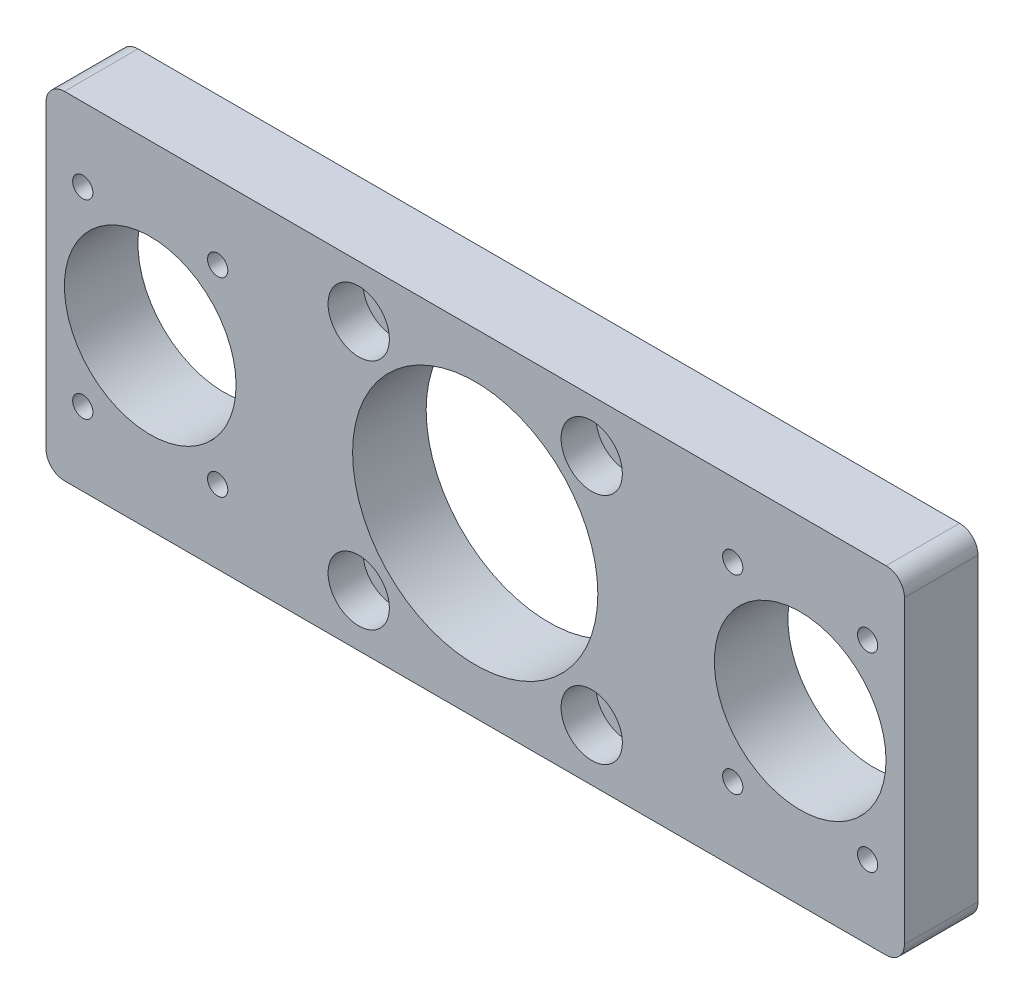
SolidWorks part; units mm, degrees
ref_plane "Front" through (0, 0, 0) normal (0, 0, 1) x (1, 0, 0)
ref_plane "Top" through (0, 0, 0) normal (0, 1, 0) x (1, 0, 0)
ref_plane "Right" through (0, 0, 0) normal (1, 0, 0) x (0, 0, -1)
sketch "草图1" plane through (0, 0, 0) normal (0, 0, 1) x (1, 0, 0)
  line L1 (-70, -27.5) -> (70, -27.5)
  line L2 (-70, -27.5) -> (-70, 27.5)
  line L3 (-70, 27.5) -> (70, 27.5)
  line L4 (70, -27.5) -> (70, 27.5)
  line L5 (-70, -27.5) -> (70, 27.5) construction
  line L6 (-70, 27.5) -> (70, -27.5) construction
  point P0 (0, 0)
  dimension "D1" = 55
  dimension "D2" = 140
extrude "凸台-拉伸1" add sketch "草图1" along normal blind 12
sketch "草图2" plane through (0, 0, 12) normal (0, 0, 1) x (1, 0, 0)
  line L0 (-70, 27.5) -> (-70, -27.5) construction
  line L1 (70, -27.5) -> (70, 27.5) construction
  circle A0 centre (0, 0) radius 20
  circle A1 centre (-53, 0) radius 14
  circle A2 centre (53, 0) radius 14
  dimension "D1" = 40
  dimension "D2" = 28
  dimension "D3" = 28
  dimension "D4" = 17
  dimension "D5" = 17
extrude "切除-拉伸1" cut sketch "草图2" against normal through all
fillet "圆角1" radius 3 4 edges at (70, 27.5, 6) (70, -27.5, 6) (-70, -27.5, 6) (-70, 27.5, 6)
sketch "草图3" plane through (0, 0, 12) normal (0, 0, 1) x (1, 0, 0)
  line L1 (-64, -15.5) -> (-42, -15.5) construction
  line L2 (-64, -15.5) -> (-64, 15.5) construction
  line L3 (-64, 15.5) -> (-42, 15.5) construction
  line L4 (-42, -15.5) -> (-42, 15.5) construction
  line L5 (-64, -15.5) -> (-42, 15.5) construction
  line L6 (-64, 15.5) -> (-42, -15.5) construction
  line L7 (42, -15.5) -> (64, -15.5) construction
  line L8 (42, -15.5) -> (42, 15.5) construction
  line L9 (42, 15.5) -> (64, 15.5) construction
  line L10 (64, -15.5) -> (64, 15.5) construction
  line L11 (42, -15.5) -> (64, 15.5) construction
  line L12 (42, 15.5) -> (64, -15.5) construction
  point P0 (-53, 0)
  point P6 (53, 0)
  dimension "D1" = 22
  dimension "D2" = 31
  dimension "D3" = 22
  dimension "D4" = 31
hole_wizard "M4 螺纹孔1" positions "草图4" profile "草图5" tap size "M4" standard "GB" end condition through all
sketch "草图4" plane through (0, 0, 12) normal (0, 0, 1) x (1, 0, 0)
  point P0 (-64, 15.5)
  point P3 (-42, 15.5)
  point P6 (-42, -15.5)
  point P9 (-64, -15.5)
  point P12 (42, -15.5)
  point P15 (64, -15.5)
  point P18 (64, 15.5)
  point P21 (42, 15.5)
sketch "草图5" plane through (-64, 15.5, 12) normal (1, 0, 0) x (0, -1, 0)
  line L0 (0, 0) -> (0, 12)
  line L1 (0, 12) -> (1.65, 12)
  line L2 (1.65, 12) -> (1.65, 0)
  line L5 (1.65, 0) -> (0, 0)
  line L11 (0, -6.35) -> (0, 107.95) construction
  dimension "通孔螺纹孔钻头直径" = 3.3
  dimension "通孔螺纹孔钻头深度" = 12
cosmetic thread "孔螺蚊线1" parameters "D2"=4
cosmetic thread "孔螺蚊线2" parameters "D2"=4
cosmetic thread "孔螺蚊线3" parameters "D2"=4
cosmetic thread "孔螺蚊线4" parameters "D2"=4
cosmetic thread "孔螺蚊线5" parameters "D2"=4
cosmetic thread "孔螺蚊线6" parameters "D2"=4
cosmetic thread "孔螺蚊线7" parameters "D2"=4
cosmetic thread "孔螺蚊线8" parameters "D2"=4
sketch "草图6" plane through (0, 0, 12) normal (0, 0, 1) x (1, 0, 0)
  line L1 (-19, -19) -> (19, -19) construction
  line L2 (-19, -19) -> (-19, 19) construction
  line L3 (-19, 19) -> (19, 19) construction
  line L4 (19, -19) -> (19, 19) construction
  line L5 (-19, -19) -> (19, 19) construction
  line L6 (-19, 19) -> (19, -19) construction
  point P0 (0, 0)
  dimension "D1" = 38
  dimension "D2" = 38
hole_wizard "打孔尺寸(%根据)内六角圆柱头螺钉的类型1" positions "草图7" profile "草图9" counterbore size "M5" standard "GB" end condition through all
sketch "草图7" plane through (0, 0, 12) normal (0, 0, 1) x (1, 0, 0)
  point P0 (-19, 19)
  point P3 (19, 19)
  point P6 (19, -19)
  point P9 (-19, -19)
sketch "草图9" plane through (-19, 19, 12) normal (1, 0, 0) x (0, -1, 0)
  line L0 (0, 0) -> (0, 12)
  line L1 (0, 12) -> (2.75, 12)
  line L3 (2.75, 12) -> (2.75, 5.7)
  line L4 (2.75, 5.7) -> (5, 5.7)
  line L5 (5, 5.7) -> (5, 0)
  line L7 (5, 0) -> (0, 0)
  line L11 (0, -6.35) -> (0, 107.95) construction
  dimension "通孔孔直径" = 5.5
  dimension "通孔孔深度" = 12
  dimension "柱形沉头孔直径" = 10
  dimension "柱形沉头孔深度" = 5.7
